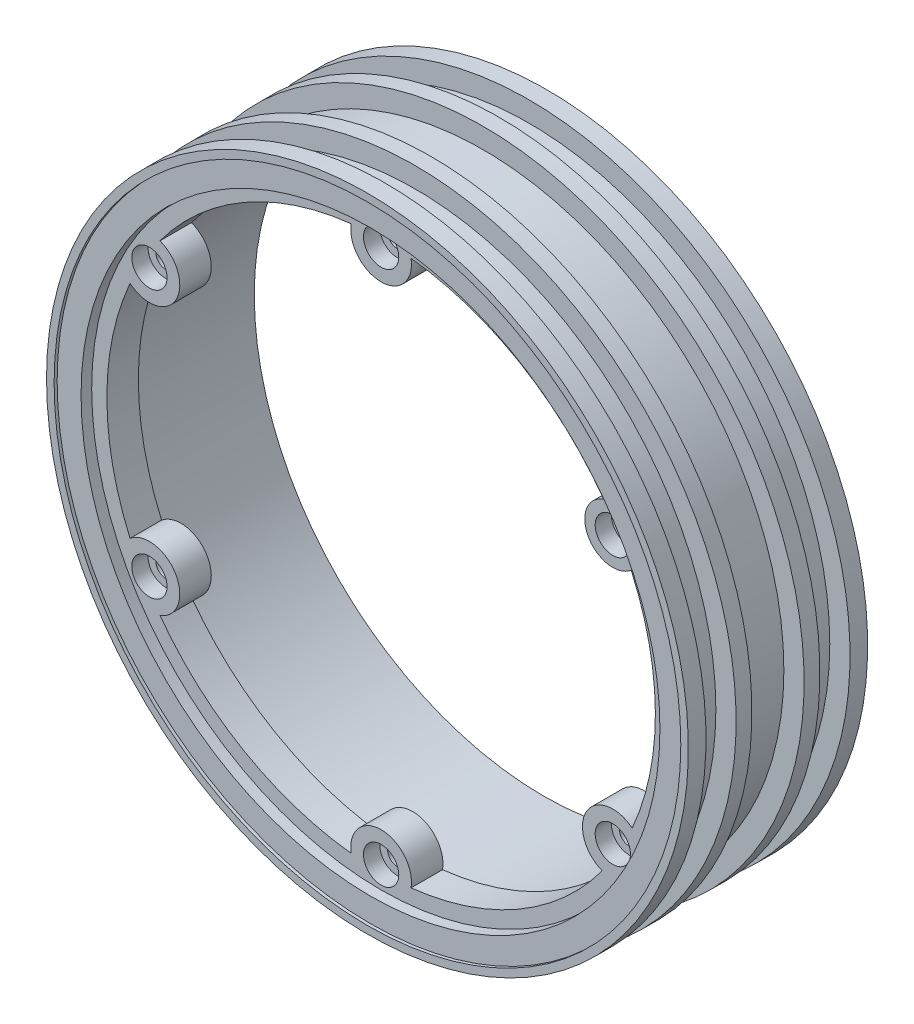
SolidWorks part; units mm, degrees
ref_plane "Piano frontale" through (0, 0, 0) normal (0, 0, 1) x (1, 0, 0)
ref_plane "Piano superiore" through (0, 0, 0) normal (0, 1, 0) x (1, 0, 0)
ref_plane "Piano destro" through (0, 0, 0) normal (1, 0, 0) x (0, 0, -1)
sketch "Schizzo1" plane through (0, 0, 0) normal (1, 0, 0) x (0, 0, -1)
  line L0 (0, 0) -> (0, 38.135) construction
  line L1 (-11.41, 38.135) -> (11.41, 38.135)
  line L2 (11.41, 38.135) -> (11.41, 41.285)
  line L3 (11.41, 41.285) -> (11.81, 41.285)
  line L4 (11.81, 41.285) -> (11.81, 42.285)
  line L5 (11.81, 42.285) -> (9.49, 42.285)
  line L6 (9.49, 42.285) -> (9.49, 39.615)
  line L7 (9.49, 39.615) -> (5.52, 39.615)
  line L8 (5.52, 39.615) -> (5.52, 42.285)
  line L9 (5.52, 42.285) -> (3.44, 42.285)
  line L10 (3.44, 42.285) -> (3.44, 39.615)
  line L11 (3.44, 39.615) -> (-3.44, 39.615)
  line L12 (0, 38.135) -> (0, 48.0242) construction
  line L13 (-3.44, 42.285) -> (-3.44, 39.615)
  line L14 (-5.52, 42.285) -> (-3.44, 42.285)
  line L15 (-5.52, 39.615) -> (-5.52, 42.285)
  line L16 (-9.49, 39.615) -> (-5.52, 39.615)
  line L17 (-9.49, 42.285) -> (-9.49, 39.615)
  line L18 (-11.81, 42.285) -> (-9.49, 42.285)
  line L19 (-11.81, 41.285) -> (-11.81, 42.285)
  line L20 (-11.41, 41.285) -> (-11.81, 41.285)
  line L21 (-11.41, 38.135) -> (-11.41, 41.285)
  line L22 (0, 0) -> (-35.9584, 0) construction
  point P16 (0, 39.615)
  dimension "D1" = 23.62
  dimension "D2" = 0.4
  dimension "D3" = 3.97
  dimension "D4" = 6.88
  dimension "D5" = 2.67
  dimension "D6" = 2.32
  dimension "D7" = 4.15
  dimension "D8" = 1
  dimension "D9" = 84.57
revolve "Rivoluzione1" add sketch "Schizzo1" angle 360 about L22
ref_plane "Piano1" through (0, 0, 10.01) normal (0, 0, 1) x (1, 0, 0)
sketch "Schizzo2" plane through (0, 0, 10.01) normal (0, 0, 1) x (1, 0, 0)
  circle A0 centre (0, 0) radius 38.135 construction
  circle A1 centre (0, 0) radius 38.135
  arc A2 (-33.0787, 14.5443) -> (-33.0787, -14.5443) centre (0, 0) ccw
  circle A3 centre (0, 0) radius 35.25 construction
  circle A4 centre (0, 35.25) radius 1.3
  arc A5 (-3.9436, 35.9192) -> (3.9436, 35.9192) centre (0, 35.25) ccw
  arc A6 (33.0787, -14.5443) -> (32.9493, 14.8351) centre (0, 0) ccw
  circle A7 centre (30.5274, 17.625) radius 1.3
  arc A8 (33.0787, -14.5443) -> (29.1351, -21.3749) centre (30.5274, -17.625) ccw
  circle A9 centre (30.5274, -17.625) radius 1.3
  arc A10 (3.9436, -35.9192) -> (-3.9436, -35.9192) centre (0, -35.25) ccw
  circle A11 centre (0, -35.25) radius 1.3
  arc A12 (-29.1351, -21.3749) -> (-33.0787, -14.5443) centre (-30.5274, -17.625) ccw
  circle A13 centre (-30.5274, -17.625) radius 1.3
  arc A14 (-33.0787, 14.5443) -> (-29.1351, 21.3749) centre (-30.5274, 17.625) ccw
  circle A15 centre (-30.5274, 17.625) radius 1.3
  circle A16 centre (0, 0) radius 36.135 construction
  arc A17 (29.3223, 21.1174) -> (32.9493, 14.8351) centre (30.5274, 17.625) ccw
  arc A18 (-3.9436, 35.9192) -> (-29.1351, 21.3749) centre (0, 0) ccw
  arc A19 (33.8202, 15.3539) -> (33.0576, 20.7231) centre (30.5274, 17.625) ccw [skipped]
  arc A20 (29.3223, 21.1174) -> (3.9436, 35.9192) centre (0, 0) ccw
  arc A21 (3.9436, -35.9192) -> (29.1351, -21.3749) centre (0, 0) ccw
  arc A22 (-29.1351, -21.3749) -> (-3.9436, -35.9192) centre (0, 0) ccw
  point P27 (0, 0)
  dimension "D2" = 70.5
  dimension "D3" = 2.6
  dimension "D4" = 8
  dimension "D1" = 2
  dimension "D5" = 6
extrude "Estrusione-Estrusione1" add sketch "Schizzo2" against normal blind 4.15
sketch "Schizzo3" plane through (0, 0, 10.01) normal (0, 0, -1) x (-1, 0, 0)
  circle A0 centre (30.5274, -17.625) radius 2.325
  circle A1 centre (0, -35.25) radius 2.325
  circle A2 centre (-30.5274, -17.625) radius 2.325
  circle A3 centre (-30.5274, 17.625) radius 2.325
  circle A4 centre (0, 35.25) radius 2.325
  circle A5 centre (30.5274, 17.625) radius 2.325
  point P16 (0, 0)
  dimension "D1" = 4.65
  dimension "D2" = 6
extrude "Taglio-Estrusione1" cut sketch "Schizzo3" along normal blind 2.15
